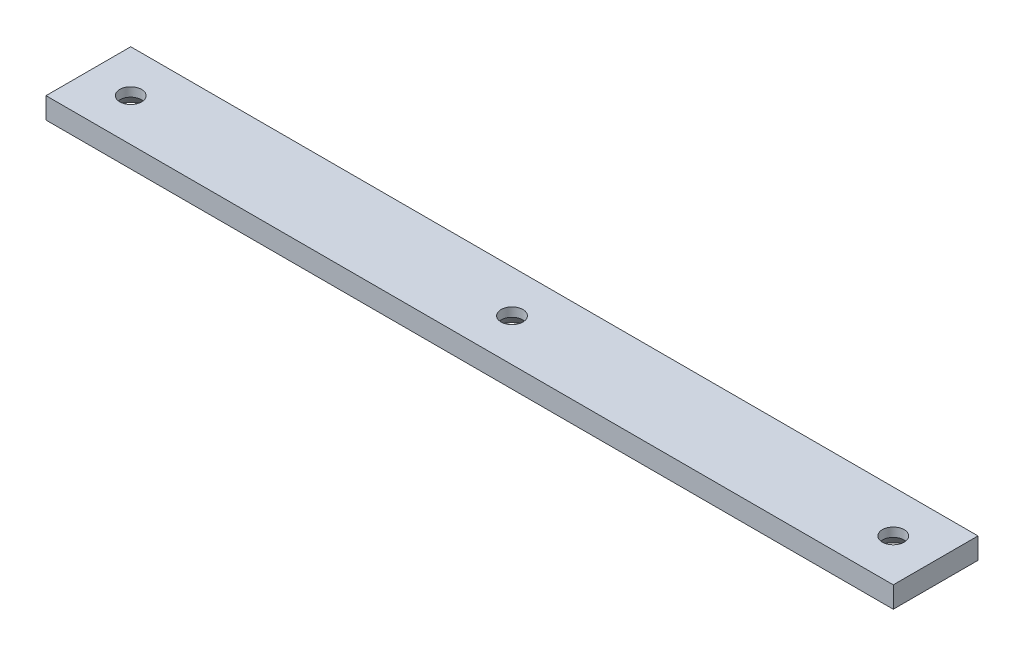
SolidWorks part; units mm, degrees
material "6061 Alloy"
ref_plane "Front Plane" through (0, 0, 0) normal (0, 0, 1) x (1, 0, 0)
ref_plane "Top Plane" through (0, 0, 0) normal (0, 1, 0) x (1, 0, 0)
ref_plane "Right Plane" through (0, 0, 0) normal (1, 0, 0) x (0, 0, -1)
sketch "Sketch1" plane through (0, 0, 0) normal (0, 1, 0) x (1, 0, 0)
  line L1 (0, 0) -> (-254, 0)
  line L2 (0, 0) -> (0, 25.4)
  line L3 (0, 25.4) -> (-254, 25.4)
  line L4 (-254, 0) -> (-254, 25.4)
  dimension "D2" = 25.4
  dimension "D1" = 254
extrude "Boss-Extrude1" add sketch "Sketch1" along normal blind 6.35
sketch "Sketch2" plane through (0, 6.35, 0) normal (0, 1, 0) x (1, 0, 0)
  line L0 (-127, 12.7) -> (-127, 25.4) construction
  line L1 (0, 25.4) -> (-254, 25.4) construction
  line L2 (-127, 12.7) -> (-127, 0) construction
  line L3 (-254, 0) -> (0, 0) construction
  circle A0 centre (-127, 12.7) radius 5.08
  dimension "D1" = 10.16
extrude "1/2-20 thread thru" [suppressed] cut sketch "Sketch2" against normal through all
sketch "Sketch3" plane through (0, 0, 0) normal (0, -1, 0) x (1, 0, 0)
  line L0 (-254, -12.7) -> (-215.9635, -12.7) construction
  line L1 (-254, -25.4) -> (-254, 0) construction
  line L2 (-254, -12.7) -> (-198.0565, -12.7) construction
  line L3 (0, -12.7) -> (-38.0365, -12.7) construction
  line L4 (0, 0) -> (0, -25.4) construction
  line L5 (0, -12.7) -> (-55.9435, -12.7) construction
  circle A0 centre (-38.0365, -12.7) radius 2.0193
  circle A1 centre (-55.9435, -12.7) radius 2.0193
  circle A2 centre (-215.9635, -12.7) radius 2.0193
  circle A3 centre (-198.0565, -12.7) radius 2.0193
  dimension "D3" = 4.0386
  dimension "D1" = 38.0365
  dimension "D2" = 55.9435
extrude "Cut-Extrude3" [suppressed] cut sketch "Sketch3" against normal blind 10.16
sketch "Sketch4" [suppressed] plane through (0, 0, 0) normal (0, -1, 0) x (1, 0, 0)
  line L0 (-127, -12.7) -> (-211.4804, -12.7) construction
  line L1 (-127, -12.7) -> (-42.5196, -12.7) construction
  circle A0 centre (-211.4804, -12.7) radius 4.1021
  circle A1 centre (-42.5196, -12.7) radius 4.1021
  dimension "D2" = 8.2042
  dimension "D1" = 84.4804
extrude "Cut-Extrude4" [suppressed] cut sketch "Sketch4" against normal through all
hole_wizard "CSK for 1/4 Flat Head Machine Screw1" positions "Sketch6" profile "Sketch7" countersink size "1/4" standard "ANSI Inch" end condition through all
sketch "Sketch6" plane through (0, 0, 0) normal (0, -1, 0) x (-1, 0, 0)
  line L0 (254, 25.4) -> (254, 0) construction
  line L2 (0, 25.4) -> (254, 25.4) construction
  line L3 (254, 0) -> (0, 0) construction
  line L4 (0, 0) -> (0, 25.4) construction
  point P0 (241.3, 12.7)
  point P3 (12.7, 12.7)
  point P23 (127, 12.7)
  dimension "D1" = 12.7
  dimension "D2" = 12.7
  dimension "D3" = 12.7
  dimension "D4" = 12.7
  dimension "D5" = 127
  dimension "D6" = 12.7
sketch "Sketch7" plane through (-241.3, 0, -12.7) normal (1, 0, 0) x (0, 0, -1)
  line L0 (0, 0) -> (0, 6.35)
  line L1 (0, 6.35) -> (3.2639, 6.35)
  line L2 (3.2639, 6.35) -> (3.2639, 3.6524)
  line L3 (3.2639, 3.6524) -> (6.4389, 0)
  line L5 (6.4389, 0) -> (0, 0)
  line L6 (-3.2639, 3.6524) -> (-6.4389, 0) construction
  line L11 (0, -6.35) -> (0, 107.95) construction
  dimension "Thru Hole Dia." = 6.5278
  dimension "Thru Hole Depth" = 6.35
  dimension "Near C'Sink Dia." = 12.8778
  dimension "Near C'Sink Angle" = 82
hole_wizard "1/2-20 Tapped Hole3" positions "Sketch14" profile "Sketch15" tap size "1/2-20" standard "ANSI Inch"
sketch "Sketch14" [suppressed] plane through (0, 12.7, 0) normal (0, 1, 0) x (1, 0, 0)
  point P0 (-127, 12.7)
sketch "Sketch15" plane through (-127, 12.7, -12.7) normal (1, 0, 0) x (0, 0, 1)
  line L0 (0, 0) -> (0, 12.7)
  line L1 (0, 12.7) -> (5.7544, 12.7)
  line L2 (5.7544, 12.7) -> (5.7544, 0)
  line L5 (5.7544, 0) -> (0, 0)
  line L11 (0, -6.35) -> (0, 107.95) construction
  dimension "Thru Tap Drill Dia." = 11.5087
  dimension "Thru Tap Drill Depth" = 12.7
cosmetic thread "Hole Thread1"
sketch3d "Sketch_MAC1-1_TOPBEAM_MILLING" [suppressed]
  line L0 (-254, 0, -25.4) -> (-244, 0, -25.4)
  line L1 (-254, 0, -25.4) -> (-254, 0, -15.4)
  point P0 (-254, 0, -25.4)
  point P1 (-244, 0, -25.4)
  point P2 (-254, 0, -15.4)
sketch3d "Stock_TOPBEAM_MILLING"
  line L0 (-254, 12.7, -25.4) -> (0, 12.7, -25.4)
  line L1 (0, 12.7, -25.4) -> (0, 12.7, 0)
  line L2 (0, 12.7, 0) -> (-254, 12.7, 0)
  line L3 (-254, 12.7, 0) -> (-254, 12.7, -25.4)
  line L4 (-254, 0, -25.4) -> (0, 0, -25.4)
  line L5 (0, 0, -25.4) -> (0, 0, 0)
  line L6 (0, 0, 0) -> (-254, 0, 0)
  line L7 (-254, 0, 0) -> (-254, 0, -25.4)
  line L8 (-254, 12.7, -25.4) -> (-254, 0, -25.4)
  line L9 (0, 12.7, -25.4) -> (0, 0, -25.4)
  line L10 (0, 12.7, 0) -> (0, 0, 0)
  line L11 (-254, 12.7, 0) -> (-254, 0, 0)
  point P8 (-127, 12.7, -25.4)
  point P9 (0, 12.7, -12.7)
  point P10 (-127, 12.7, 0)
  point P11 (-254, 12.7, -12.7)
  point P12 (-127, 0, -25.4)
  point P13 (0, 0, -12.7)
  point P14 (-127, 0, 0)
  point P15 (-254, 0, -12.7)
  point P16 (-254, 6.35, -25.4)
  point P17 (0, 6.35, -25.4)
  point P18 (0, 6.35, 0)
  point P19 (-254, 6.35, 0)
  point P20 (-127, 6.35, -12.7)
  point P21 (-127, 6.35, -25.4)
  point P22 (-127, 0, -12.7)
  point P23 (-127, 6.35, 0)
  point P24 (-127, 12.7, -12.7)
  point P25 (-254, 6.35, -12.7)
  point P26 (0, 6.35, -12.7)
equation "\"cross_length\"=10"
equation "\"wing_spar_height\"= 2"
equation "\"wing_spar_thickness\"= .5"
equation "\"frame_width\"= 10"
equation "\"D1@Sketch1\"=\"frame_width\""
